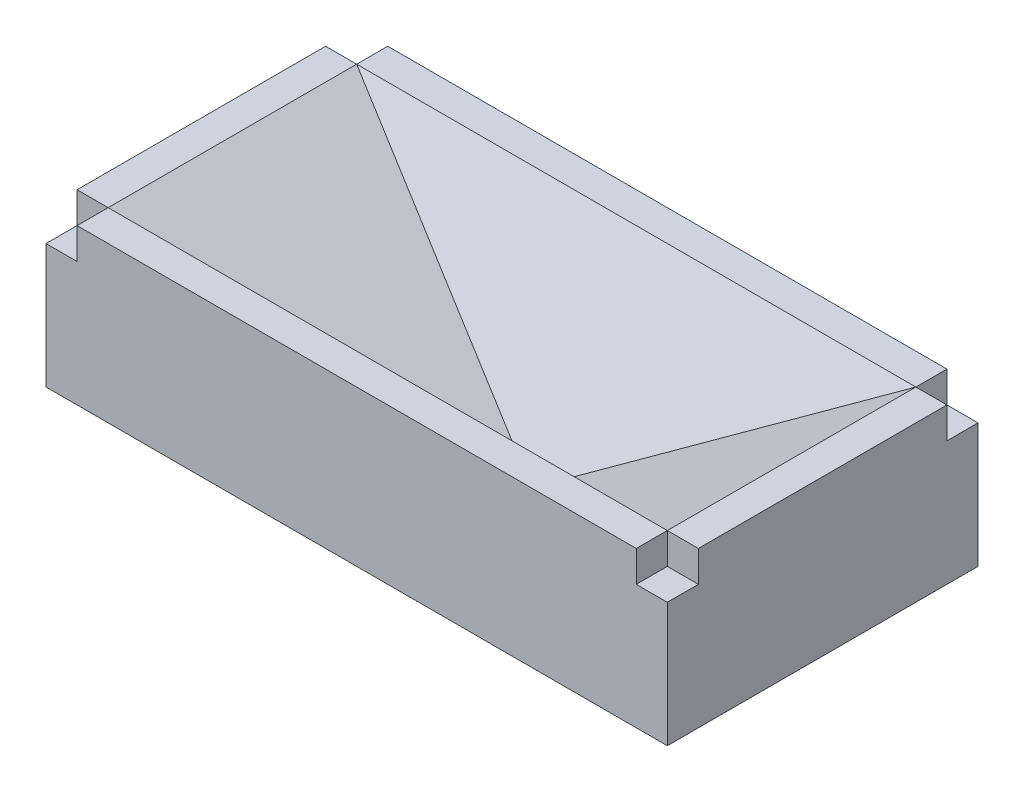
SolidWorks part; units mm, degrees
ref_plane "Front Plane" through (0, 0, 0) normal (0, 0, 1) x (1, 0, 0)
ref_plane "Top Plane" through (0, 0, 0) normal (0, 1, 0) x (1, 0, 0)
ref_plane "Right Plane" through (0, 0, 0) normal (1, 0, 0) x (0, 0, -1)
sketch "Sketch2" plane through (0, 0, 0) normal (0, 1, 0) x (1, 0, 0)
  line L1 (-50, 25) -> (50, 25)
  line L2 (-50, 25) -> (-50, -25)
  line L3 (-50, -25) -> (50, -25)
  line L4 (50, 25) -> (50, -25)
  line L5 (-50, 25) -> (50, -25) construction
  line L6 (-50, -25) -> (50, 25) construction
  point P0 (0, 0)
  dimension "D1" = 50
  dimension "D2" = 100
extrude "Boss-Extrude1" add sketch "Sketch2" against normal blind 25
sketch "Sketch3" plane through (0, 0, 0) normal (0, 1, 0) x (1, 0, 0)
  line L1 (-45, 20) -> (45, 20)
  line L2 (-45, 20) -> (-45, -20)
  line L3 (-45, -20) -> (45, -20)
  line L4 (45, 20) -> (45, -20)
  line L5 (-45, 20) -> (45, -20) construction
  line L6 (-45, -20) -> (45, 20) construction
  point P0 (0, 0)
  dimension "D1" = 40
  dimension "D2" = 90
sketch "Sketch4" plane through (0, -25, 0) normal (0, -1, 0) x (1, 0, 0)
  line L1 (-5, 5) -> (5, 5)
  line L2 (-5, 5) -> (-5, -5)
  line L3 (-5, -5) -> (5, -5)
  line L4 (5, 5) -> (5, -5)
  line L5 (-5, 5) -> (5, -5) construction
  line L6 (-5, -5) -> (5, 5) construction
  point P0 (0, 0)
  dimension "D1" = 10
  dimension "D2" = 10
loft "Cut-Loft4" cut profiles "Sketch3", "Sketch4"
sketch "Sketch5" plane through (0, 0, -25) normal (0, 0, -1) x (-1, 0, 0)
  line L1 (-50, -25) -> (50, -25) construction
  line L2 (0, -8) -> (3.2, -8)
  line L3 (0, -8) -> (-3.2, -8)
  line L4 (-3.2, -8) -> (-3.2, -25)
  line L5 (-3.2, -25) -> (3.2, -25)
  line L6 (3.2, -25) -> (3.2, -8)
extrude "Cut-Extrude1" cut sketch "Sketch5" against normal blind 9
sketch "Sketch6" plane through (-3.2, 0, 0) normal (1, 0, 0) x (0, 0, -1)
  line L0 (25, -8) -> (25, -25)
  line L1 (25, -25) -> (16, -25)
  line L2 (16, -25) -> (16, -8)
  line L3 (16, -8) -> (25, -8)
  line L4 (16, -8) -> (5.7854, -25)
  line L5 (16, -25) -> (5.7854, -25)
  line M7 (16, -8) -> (16, -25)
  dimension "D1" = 31
sketch "Sketch7" plane through (-12.6404, -20.2247, 0) normal (0.53, 0.848, 0) x (0.848, -0.53, 0)
  line L0 (-38.1599, 20) -> (9.01, 5)
  line L1 (9.01, 5) -> (9.01, -5)
  line L2 (9.01, -5) -> (-38.1599, -20)
  line L3 (-38.1599, -20) -> (-38.1599, 20)
extrude "Cut-Extrude2" cut sketch "Sketch6" along normal blind 6.4 contours L5 L4 M7
sketch "Sketch8" plane through (0, -25, 0) normal (0, -1, 0) x (1, 0, 0)
  line L0 (-50, 25) -> (-50, 15)
  line L1 (-50, -25) -> (-50, 25) construction
  line L2 (-50, 15) -> (-40, 15)
  line L3 (-40, 15) -> (-40, 25)
  line L4 (-50, 25) -> (50, 25) construction
  line L5 (-40, 25) -> (-50, 25)
  line L6 (50, 25) -> (50, 15)
  line L7 (50, 25) -> (50, -25) construction
  line L8 (50, 15) -> (40, 15)
  line L9 (40, 15) -> (40, 25)
  line L10 (40, 25) -> (50, 25)
  line L11 (-50, 15) -> (-45, 15)
  line L12 (-45, 15) -> (-45, 20)
  line L13 (45, 15) -> (45, 20)
  line L14 (-48, 23) -> (-42, 23)
  line L15 (-48, 23) -> (-48, 17)
  line L16 (-48, 17) -> (-42, 17)
  line L17 (-42, 23) -> (-42, 17)
  line L18 (-48, 23) -> (-42, 17) construction
  line L19 (-48, 17) -> (-42, 23) construction
  line L20 (40, 25) -> (50, 25)
  line L21 (48, 23) -> (42, 23)
  line L22 (48, 23) -> (48, 17)
  line L23 (48, 17) -> (42, 17)
  line L24 (42, 23) -> (42, 17)
  line L25 (48, 23) -> (42, 17) construction
  line L26 (48, 17) -> (42, 23) construction
  line L27 (50, 15) -> (50, 25)
  dimension "D1" = 6
  dimension "D2" = 6
  dimension "D3" = 6
  dimension "D4" = 6
  dimension "D5" = 10
  dimension "D6" = 10
extrude "Cut-Extrude3" cut sketch "Sketch8" against normal blind 6
sketch "Sketch9" plane through (0, 0, 0) normal (0, 1, 0) x (1, 0, 0)
  line L0 (50, -25) -> (50, -20)
  line L1 (50, -25) -> (50, 25) construction
  line L2 (50, -20) -> (45, -20)
  line L3 (45, -20) -> (45, -25)
  line L4 (-50, -25) -> (50, -25) construction
  line L5 (45, -25) -> (50, -25)
  line L6 (-50, -25) -> (-50, -20)
  line L7 (-50, 25) -> (-50, -25) construction
  line L8 (-50, -20) -> (-45, -20)
  line L9 (-45, -20) -> (-45, -25)
  line L10 (-45, -25) -> (-50, -25)
  line L11 (-50, 25) -> (-45, 25)
  line L12 (50, 25) -> (-50, 25) construction
  line L13 (-45, 25) -> (-45, 20)
  line L14 (-45, 20) -> (-50, 20)
  line L15 (-50, 20) -> (-50, 25)
  line L16 (50, 25) -> (45, 25)
  line L17 (45, 25) -> (45, 20)
  line L18 (45, 20) -> (50, 20)
  line L19 (50, 20) -> (50, 25)
extrude "Cut-Extrude4" cut sketch "Sketch9" against normal blind 5
